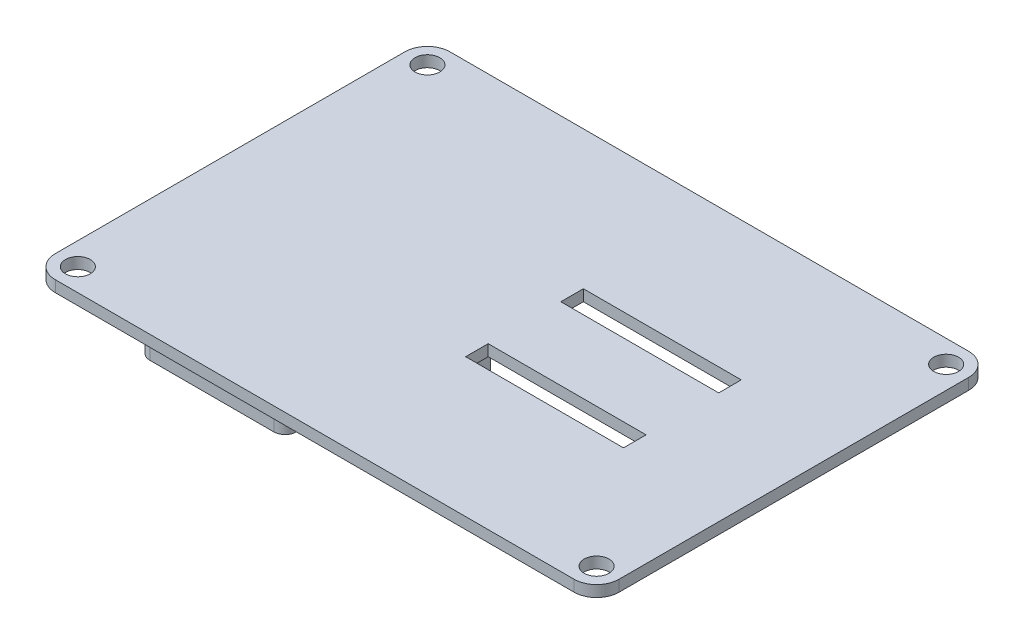
SolidWorks part; units mm, degrees
ref_plane "Front Plane" through (0, 0, 0) normal (0, 0, 1) x (1, 0, 0)
ref_plane "Top Plane" through (0, 0, 0) normal (0, 1, 0) x (1, 0, 0)
ref_plane "Right Plane" through (0, 0, 0) normal (1, 0, 0) x (0, 0, -1)
sketch "Sketch1" plane through (0, 0, 0) normal (0, 1, 0) x (1, 0, 0)
  line L1 (-63.5, -44.45) -> (63.5, -44.45)
  line L2 (-63.5, -44.45) -> (-63.5, 44.45)
  line L3 (-63.5, 44.45) -> (63.5, 44.45)
  line L4 (63.5, -44.45) -> (63.5, 44.45)
  line L5 (-63.5, -44.45) -> (63.5, 44.45) construction
  line L6 (-63.5, 44.45) -> (63.5, -44.45) construction
  point P0 (0, 0)
  dimension "D1" = 88.9
  dimension "D2" = 127
extrude "Boss-Extrude2" add sketch "Sketch1" along normal blind 2.54
sketch "Sketch2" plane through (0, 0, 0) normal (0, -1, 0) x (-1, 0, 0)
  line L1 (-58.42, 39.37) -> (58.42, 39.37)
  line L2 (-58.42, 39.37) -> (-58.42, -39.37)
  line L3 (-58.42, -39.37) -> (58.42, -39.37)
  line L4 (58.42, 39.37) -> (58.42, -39.37)
  line L5 (-58.42, 39.37) -> (58.42, -39.37) construction
  line L6 (-58.42, -39.37) -> (58.42, 39.37) construction
  circle A0 centre (58.42, 39.37) radius 2.794
  circle A1 centre (58.42, -39.37) radius 2.794
  circle A2 centre (-58.42, -39.37) radius 2.794
  circle A3 centre (-58.42, 39.37) radius 2.794
  point P0 (0, 0)
  dimension "D3" = 5.588
  dimension "D4" = 5.588
  dimension "D5" = 5.588
  dimension "D6" = 5.588
  dimension "D1" = 116.84
  dimension "D2" = 78.74
extrude "Cut-Extrude1" cut sketch "Sketch2" against normal blind 5.08 contours A0 | A1 | A2 | A3
sketch "Sketch8" plane through (0, 0, 0) normal (0, -1, 0) x (-1, 0, 0)
  line L1 (58.7259, -25.4) -> (25.7059, -25.4)
  line L2 (58.7259, -25.4) -> (58.7259, 27.94)
  line L3 (58.7259, 27.94) -> (25.7059, 27.94)
  line L4 (25.7059, -25.4) -> (25.7059, 27.94)
  line L5 (58.7259, -25.4) -> (25.7059, 27.94) construction
  line L6 (58.7259, 27.94) -> (25.7059, -25.4) construction
  point P0 (42.2159, 1.27)
  dimension "D1" = 33.02
  dimension "D2" = 53.34
sketch "Sketch9" plane through (0, 0, 0) normal (0, -1, 0) x (-1, 0, 0)
  line L0 (0, 44.45) -> (0, -44.45) construction
  line L1 (-63.5, 44.45) -> (63.5, 44.45) construction
  line L2 (63.5, -44.45) -> (-63.5, -44.45) construction
  line L3 (-63.5, 0) -> (63.5, 0) construction
  line L4 (-63.5, -44.45) -> (-63.5, 44.45) construction
  line L5 (63.5, 44.45) -> (63.5, -44.45) construction
  line L6 (-2.8155, -13.2599) -> (-2.8155, -8.1799)
  line L7 (-38.3755, 13.2599) -> (-2.8155, 13.2599)
  line L8 (-38.3755, 13.2599) -> (-38.3755, 8.1799)
  line L9 (-38.3755, 8.1799) -> (-2.8155, 8.1799)
  line L10 (-2.8155, 13.2599) -> (-2.8155, 8.1799)
  line L11 (-38.3755, 13.2599) -> (-2.8155, 8.1799) construction
  line L12 (-38.3755, 8.1799) -> (-2.8155, 13.2599) construction
  line L13 (-38.3755, -8.1799) -> (-2.8155, -8.1799)
  line L14 (-38.3755, -13.2599) -> (-38.3755, -8.1799)
  line L15 (-38.3755, -13.2599) -> (-2.8155, -13.2599)
  point P12 (-20.5955, 10.7199)
  dimension "D1" = 35.56
  dimension "D2" = 5.08
extrude "Cut-Extrude5" cut sketch "Sketch9" against normal blind 6.35
extrude "Boss-Extrude4" add sketch "Sketch8" along normal blind 21.59 separate body
shell "Shell4" thickness 2.54
sketch "Sketch13" plane through (0, 0, -27.94) normal (0, 0, -1) x (-1, 0, 0)
  line L0 (42.2159, 0) -> (42.2159, -21.59) construction
  line L1 (58.7259, 0) -> (25.7059, 0) construction
  line L2 (58.7259, -21.59) -> (25.7059, -21.59) construction
  line L3 (58.7259, -10.795) -> (25.7059, -10.795) construction
  line L4 (58.7259, -21.59) -> (58.7259, 0) construction
  line L5 (25.7059, -21.59) -> (25.7059, 0) construction
  line L7 (54.5224, -3.7461) -> (29.9095, -3.7461)
  line L8 (54.5224, -3.7461) -> (54.5224, -17.8439)
  line L9 (54.5224, -17.8439) -> (29.9095, -17.8439)
  line L10 (29.9095, -3.7461) -> (29.9095, -17.8439)
  line L11 (54.5224, -3.7461) -> (29.9095, -17.8439) construction
  line L12 (54.5224, -17.8439) -> (29.9095, -3.7461) construction
  point P12 (42.2159, -10.795)
extrude "Cut-Extrude6" cut sketch "Sketch13" against normal blind 5.08
fillet "Fillet5" radius 2.54 1 edges at (-29.9095, -17.8439, -26.67)
fillet "Fillet6" radius 2.54 1 edges at (-29.9095, -3.7461, -26.67)
fillet "Fillet7" radius 2.54 1 edges at (-54.5224, -3.7461, -26.67)
fillet "Fillet8" radius 2.54 1 edges at (-54.5224, -17.8439, -26.67)
fillet "Fillet1" radius 5.08 1 edges at (63.5, 1.27, 44.45)
fillet "Fillet2" radius 5.08 1 edges at (-63.5, 1.27, -44.45)
fillet "Fillet3" radius 5.08 1 edges at (-63.5, 1.27, 44.45)
fillet "Fillet4" radius 5.08 1 edges at (63.5, 1.27, -44.45)
fillet "Fillet9" radius 2.54 1 edges at (-25.7059, -10.795, -27.94)
fillet "Fillet10" radius 2.54 1 edges at (-25.7059, -10.795, 25.4)
fillet "Fillet11" radius 2.54 1 edges at (-58.7259, -10.795, 25.4)
fillet "Fillet12" radius 2.54 1 edges at (-58.7259, -10.795, -27.94)
sketch "Sketch17" plane through (0, 0, 0) normal (0, -1, 0) x (-1, 0, 0)
  line L0 (-63.5, 37.465) -> (63.5, 37.465) construction
  line L1 (-63.5, -39.37) -> (-63.5, 39.37) construction
  line L2 (63.5, 39.37) -> (63.5, -39.37) construction
  line L3 (-58.42, 44.45) -> (58.42, 44.45) construction
  line L5 (-44.6949, 37.465) -> (1.0251, 37.465) construction
  line L6 (-44.6949, 37.465) -> (-44.6949, -8.255) construction
  line L7 (-44.6949, -8.255) -> (1.0251, -8.255) construction
  line L8 (1.0251, 37.465) -> (1.0251, -8.255) construction
  line L9 (-44.6949, 37.465) -> (1.0251, -8.255) construction
  line L10 (-44.6949, -8.255) -> (1.0251, 37.465) construction
  circle A0 centre (1.0251, -8.255) radius 3.175
  circle A1 centre (1.0251, 37.465) radius 3.175
  circle A2 centre (-44.6949, 37.465) radius 3.175
  circle A3 centre (-44.6949, -8.255) radius 3.175
  point P12 (-21.8349, 14.605)
  point P18 (-44.6949, -8.255)
  point P19 (-44.6949, 37.465)
  point P20 (1.0251, 37.465)
  point P21 (1.0251, -8.255)
  point P22 (-44.6949, -8.255)
  point P23 (-44.6949, 37.465)
  point P24 (1.0251, -8.255)
  point P25 (1.0251, 37.465)
  dimension "D4" = 6.35
  dimension "D5" = 6.35
  dimension "D6" = 6.35
  dimension "D7" = 6.35
  dimension "D1" = 6.985
  dimension "D2" = 45.72
  dimension "D3" = 45.72
extrude "Boss-Extrude5" add sketch "Sketch17" along normal blind 7.62
sketch "Sketch18" plane through (0, -7.62, 0) normal (0, -1, 0) x (1, 0, 0)
  circle A0 centre (44.6949, 8.255) radius 1.651
  circle A1 centre (44.6949, -37.465) radius 1.651
  circle A2 centre (-1.0251, -37.465) radius 1.651
  circle A3 centre (-1.0251, 8.255) radius 1.651
  point P0 (-1.0251, 8.255)
  point P1 (-1.0251, -37.465)
  point P3 (44.6949, -37.465)
  point P5 (44.6949, 8.255)
  dimension "D1" = 3.302
  dimension "D2" = 3.302
  dimension "D3" = 3.302
  dimension "D4" = 3.302
extrude "Cut-Extrude7" cut sketch "Sketch18" against normal blind 5.08 draft 2 contours A0 | A1 | A2 | A3
ref_plane "Plane1" through (0, -21.59, 0) normal (0, -1, 0) x (-1, 0, 0)
sketch "Sketch20" plane through (0, -21.59, 0) normal (0, -1, 0) x (-1, 0, 0)
  line L1 (22.0351, -23.7719) -> (52.4166, -23.7719)
  line L2 (22.0351, -23.7719) -> (22.0351, -17.4219)
  line L3 (22.0351, -17.4219) -> (52.4166, -17.4219)
  line L4 (52.4166, -23.7719) -> (52.4166, -17.4219)
  dimension "D1" = 6.35
